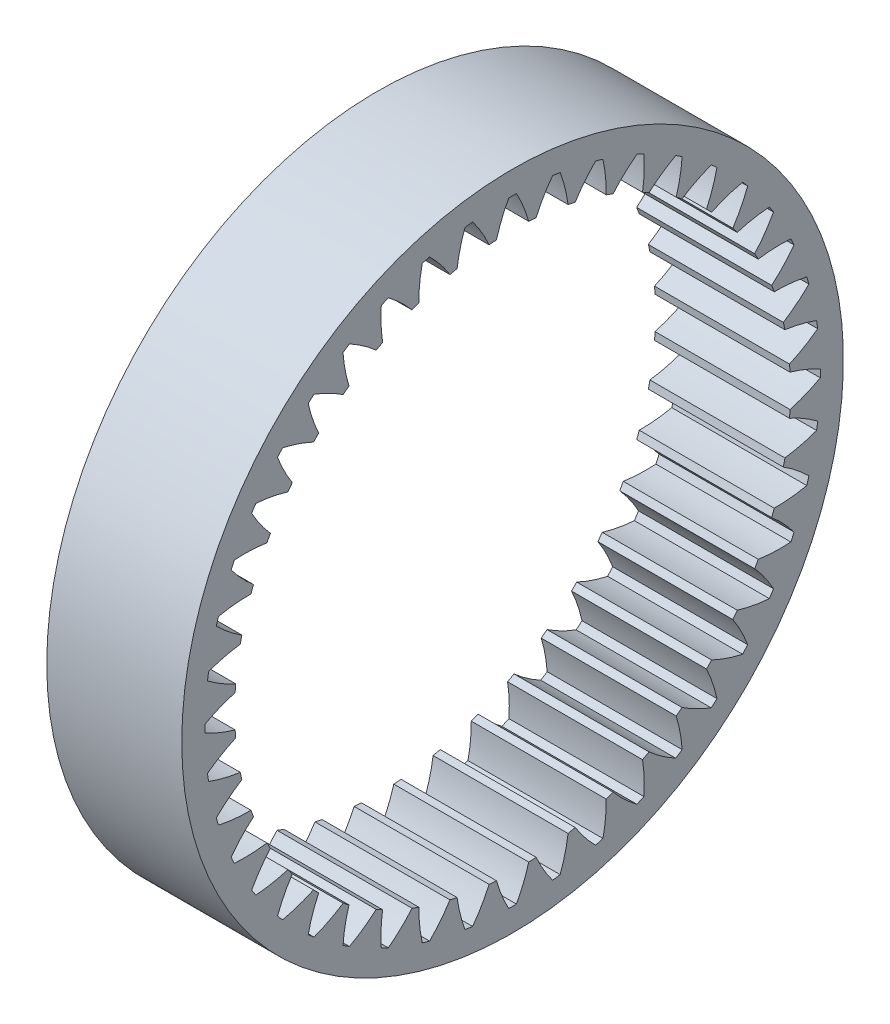
SolidWorks part; units mm, degrees
ref_plane "Plane1" through (0, 0, 0) normal (0, 0, 1) x (1, 0, 0)
ref_plane "Plane2" through (0, 0, 0) normal (0, 1, 0) x (1, 0, 0)
ref_plane "Plane3" through (0, 0, 0) normal (1, 0, 0) x (0, 0, -1)
other "Configuration Table"
sketch "HoldingSke" plane through (0, 0, 0) normal (0, 1, 0) x (1, 0, 0)
  line L0 (0, 0) -> (1.4387, -1.3893)
  line L1 (-15, 0) -> (100, 0) construction
  line L2 (0, 0) -> (-2.1039, 2.3779)
  line L3 (0, 0) -> (-11.863, 4.5341)
  line L4 (0, 0) -> (6.2122, 5.9991)
  line L5 (0, 0) -> (-23.7986, -8.8762)
  line L6 (0, 0) -> (-10.5278, -7.1032)
  line L7 (-2.1039, 2.3779) -> (3.3635, 27.1825)
  line L8 (-76.2, 2.8779) -> (-54.61, 2.8779)
  line L9 (-71.009, 38.7566) -> (-53.1078, 45.2721)
  line L10 (-76.2, 71.12) -> (104.1128, 71.12)
  line L11 (0, 0) -> (-5.1, 0)
  line L12 (-76.2, 101.6) -> (-76.181, 101.6)
  line L13 (24.9733, 27.94) -> (52.9518, 28.4284)
  line L14 (24.9733, 27.94) -> (24.9743, 27.94)
  line L15 (24.9733, 27.94) -> (100.4006, 29.5858)
  circle A0 centre (0, 0) radius 12.5
  circle A1 centre (0, 0) radius 12.7
  circle A2 centre (0, 0) radius 12.7
  dimension "MHD" = 25.4
  dimension "Hub_dia" = 25.4
  dimension "Diameter" = 25
  dimension "Num_teeth" = 44
  dimension "Pitch" = 2
  dimension "Overall_len" = 25.4
  dimension "Show_teeth" = 44
  dimension "Thickness" = 12.7
  dimension "OAL" = 25.4001
  dimension "T_dim" = 21.59
  dimension "Ap" = 20
  dimension "H" = 19.05
  dimension "Pitch_radius" = 180.3128
  dimension "Width" = 5.1
  dimension "Backlash" = 0.019
  dimension "Addendum_fac" = 1
  dimension "Dedendum_fac" = 1.25
  dimension "Clearance_fac" = 0.25
  dimension "Dedendum_add" = 0.001
  dimension "Module" = 0.5
sketch "BasProSke" plane through (0, 0, 0) normal (0, 1, 0) x (1, 0, 0)
  line L0 (-10, 0) -> (60, 0) construction
  line L1 (0, 10.5) -> (0, 12.5)
  line L2 (0, 10.5) -> (5.1, 10.5)
  line L3 (5.1, 10.5) -> (5.1, 12.5)
  line L4 (5.1, 12.5) -> (0, 12.5)
  dimension "Diameter" = 25
  dimension "Thickness" = 5.1
  dimension "Inside_diameter" = 21
revolve "Base-Revolve" add sketch "BasProSke" angle 360 about L0
sketch "TooCutSke" plane through (0, 0, 0) normal (1, 0, 0) x (0, 0, -1)
  line L3 (0.4401, 10.9912) -> (0.4401, 53.6633) construction
  line L4 (0, 0) -> (0, 59.563) construction
  line L5 (0, 0) -> (-4.8744, 68.1534) construction
  line L6 (-4.6836, 8.9917) -> (37.0827, 11.9789) construction
  circle A0 centre (0, 0) radius 11 construction
  circle A1 centre (0, 0) radius 11.626 construction
  circle A2 centre (0, 0) radius 9.303 construction
  circle A3 centre (0, 0) radius 10.4746 construction
  arc A4 (0.6178, 10.4564) -> (0.145, 11.6251) centre (-4.6836, 8.9917) ccw
  arc A5 (0.6178, 10.4564) -> (-0.6178, 10.4564) centre (0, 0) ccw
  arc A6 (0.145, 11.6251) -> (-0.145, 11.6251) centre (0, 0) ccw
  arc A7 (-0.145, 11.6251) -> (-0.6178, 10.4564) centre (4.6836, 8.9917) ccw
  dimension "Pitch_dia" = 22
  dimension "Base_dia" = 18.6059
  dimension "Root_dia" = 23.252
  dimension "Overcut_dia" = 20.9492
  dimension "Flank_rad" = 5.5
  dimension "Half_ang" = 4.091
  dimension "Half_CT" = 0.4401
extrude "ToothCut" cut sketch "TooCutSke" along normal through all
fillet "Breaks" [suppressed] radius 0.05
fillet "RootFillets" [suppressed] radius 0.126
pattern_circular "TeethCuts" count 44 every 8.182 about axis through (-10, 0, 0) along (1, 0, 0) of "RootFillets", "Breaks", "ToothCut"
equation "' \"Module@HoldingSke\" = 6.35"
equation "' \"Num_teeth@HoldingSke\" = 24"
equation "' \"Ap@HoldingSke\" =  14.5"
equation "' \"Ap@HoldingSke\" = 14.5"
equation "' \"Width@HoldingSke\" = 12"
equation "' \"Diameter@HoldingSke\" = 8 * 25.4"
equation "' \"Show_teeth@HoldingSke\" = 100"
equation "' \"Backlash@HoldingSke\" = 0.009 * 25.4"
equation "' \"Addendum_fac@HoldingSke\" = 1.0"
equation "' \"Dedendum_fac@HoldingSke\" = 1.25"
equation "' \"Dedendum_add@HoldingSke\" = 0.00005 * 25.4"
equation "' \"Clearance_fac@HoldingSke\" = 0.25"
equation "\"Pitch@HoldingSke\" = 1 / \"Module@HoldingSke\" "
equation "\"Overcut_dia@TooCutSke\" = (\"Num_teeth@HoldingSke\" - 2 * \"Addendum_fac@HoldingSke\") / \"Pitch@HoldingSke\" - 0.002 * 25.4"
equation "\"Pitch_dia@TooCutSke\" = \"Num_teeth@HoldingSke\" / \"Pitch@HoldingSke\""
equation "\"Base_dia@TooCutSke\" = \"Num_teeth@HoldingSke\" / \"Pitch@HoldingSke\" * cos((\"Ap@HoldingSke\"  * 3.14159265 / 180)) * 0.90"
equation "\"Root_dia@TooCutSke\" = \"Num_teeth@HoldingSke\"  / \"Pitch@HoldingSke\" + 2 *  \"Dedendum_fac@HoldingSke\"/ \"Pitch@HoldingSke\" + \"Dedendum_add@HoldingSke\" * 2"
equation "\"Half_ang@TooCutSke\" = 180 / \"Num_teeth@HoldingSke\""
equation "\"Half_CT@TooCutSke\" = \"Num_teeth@HoldingSke\" / \"Pitch@HoldingSke\" * sin((3.14159265 / 2 / \"Num_teeth@HoldingSke\")) / 2 + 10 * \"Backlash@HoldingSke\" / 4"
equation "\"Flank_rad@TooCutSke\" = \"Num_teeth@HoldingSke\" / \"Pitch@HoldingSke\" / 4"
equation "\"Radius@RootFillets\"= \"Clearance_fac@HoldingSke\" / \"Pitch@HoldingSke\" + \"Dedendum_add@HoldingSke\""
equation "\"Break_rad@Breaks\" = 0.02 / \"Pitch@HoldingSke\" * 5"
equation "\"Num_teeth@TeethCuts\" = int( \"Show_teeth@HoldingSke\" ) + 1"
equation "\"Num_teeth@TeethCuts\" = ((sgn( \"Num_teeth@TeethCuts\" - \"Num_teeth@HoldingSke\" )-1)*( \"Num_teeth@TeethCuts\" - \"Num_teeth@HoldingSke\" ))/-2+ \"Num_teeth@HoldingSke\""
equation "\"Num_teeth@TeethCuts\" = ((sgn( \"Num_teeth@TeethCuts\" - 2.0)+1)*( \"Num_teeth@TeethCuts\" - 2.0))/2 +2.0"
equation "\"Angle@TeethCuts\" = 360.0 / \"Num_teeth@HoldingSke\""
equation "\"Diameter@BasProSke\" = \"Num_teeth@HoldingSke\"  / \"Pitch@HoldingSke\" + 2 *  \"Dedendum_fac@HoldingSke\"/ \"Pitch@HoldingSke\" + \"Dedendum_add@HoldingSke\" * 2 + 0.002 * 25.4"
equation "\"Diameter@BasProSke\" = ((sgn( \"Diameter@BasProSke\"  - \"Diameter@HoldingSke\" )+1)*( \"Diameter@BasProSke\"  - \"Diameter@HoldingSke\" ))/2 + \"Diameter@HoldingSke\""
equation "\"Inside_diameter@BasProSke\" =  (\"Num_teeth@HoldingSke\" - 2 * \"Addendum_fac@HoldingSke\") / \"Pitch@HoldingSke\" "
equation "\"Thickness@BasProSke\"  = \"Width@HoldingSke\""
